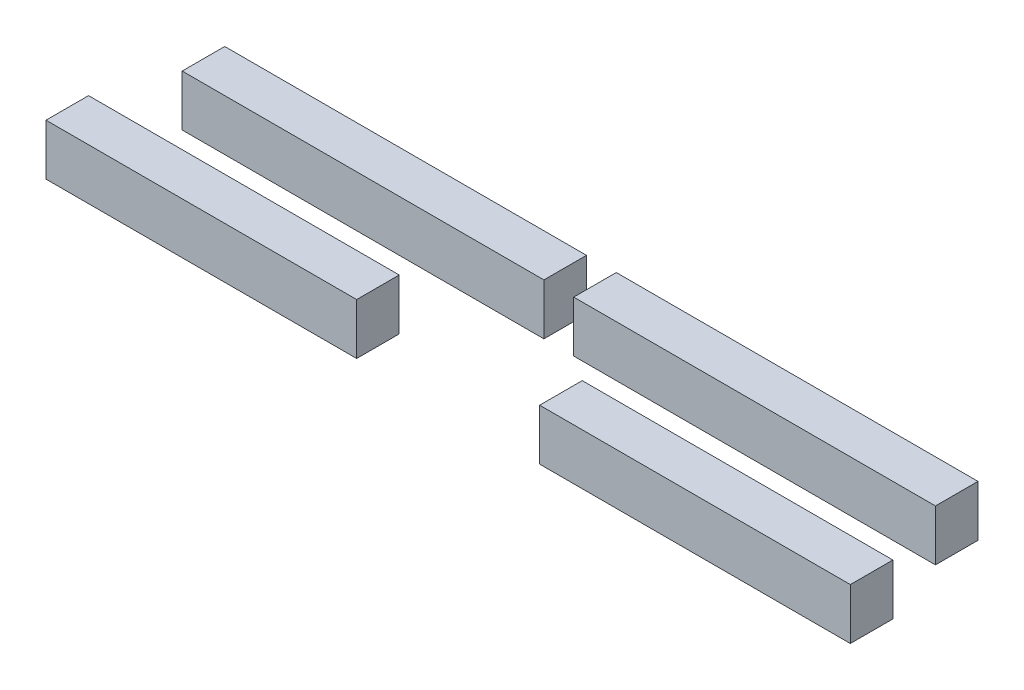
SolidWorks part; units mm, degrees
ref_plane "Front Plane" through (0, 0, 0) normal (0, 0, 1) x (1, 0, 0)
ref_plane "Top Plane" through (0, 0, 0) normal (0, 1, 0) x (1, 0, 0)
ref_plane "Right Plane" through (0, 0, 0) normal (1, 0, 0) x (0, 0, -1)
sketch "Sketch1" plane through (0, 0, 0) normal (0, 1, 0) x (1, 0, 0)
  line L0 (60.75, 9.5) -> (97.25, 9.5)
  line L1 (2.75, 9.5) -> (39.25, 9.5)
  line L2 (2.75, 9.5) -> (2.75, 4.5)
  line L3 (2.75, 4.5) -> (39.25, 4.5)
  line L4 (39.25, 9.5) -> (39.25, 4.5)
  line L5 (0, 0) -> (100, 0) construction
  line L6 (0, 0) -> (0, 75) construction
  line L7 (0, 75) -> (100, 75) construction
  line L8 (100, 0) -> (100, 75) construction
  line L9 (60.75, 9.5) -> (60.75, 4.5)
  line L10 (60.75, 4.5) -> (97.25, 4.5)
  line L11 (97.25, 9.5) -> (97.25, 4.5)
  line L12 (51.75, 22.5) -> (94.25, 22.5)
  line L13 (5.75, 22.5) -> (48.25, 22.5)
  line L14 (5.75, 22.5) -> (5.75, 17.5)
  line L15 (5.75, 17.5) -> (48.25, 17.5)
  line L16 (48.25, 22.5) -> (48.25, 17.5)
  line L17 (51.75, 22.5) -> (51.75, 17.5)
  line L18 (51.75, 17.5) -> (94.25, 17.5)
  line L19 (94.25, 22.5) -> (94.25, 17.5)
extrude "Boss-Extrude1" add sketch "Sketch1" along normal blind 6
